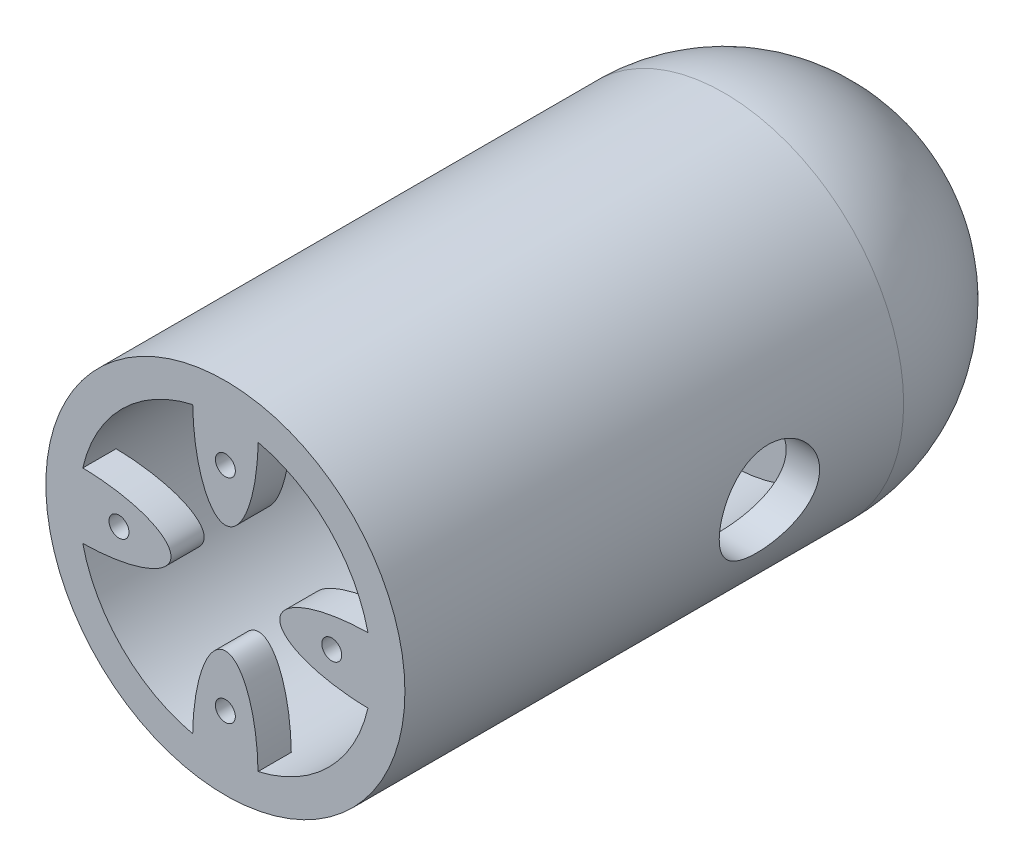
SolidWorks part; units mm, degrees
ref_plane "Front Plane" through (0, 0, 0) normal (0, 0, 1) x (1, 0, 0)
ref_plane "Top Plane" through (0, 0, 0) normal (0, 1, 0) x (1, 0, 0)
ref_plane "Right Plane" through (0, 0, 0) normal (1, 0, 0) x (0, 0, -1)
sketch "Sketch1" plane through (0, 0, 0) normal (0, 0, 1) x (1, 0, 0)
  circle A0 centre (0, 0) radius 27
  dimension "D1" = 54
extrude "Boss-Extrude1" add sketch "Sketch1" along normal mid plane 75
sketch "Sketch3" plane through (0, 0, 0) normal (1, 0, 0) x (0, 0, -1)
  line L1 (37.5, 27) -> (-37.5, 27) construction
  line L2 (37.5, -27) -> (37.5, 27) construction
  circle A0 centre (17.5, -3) radius 7.5
  dimension "D1" = 15
  dimension "D2" = 20
  dimension "D3" = 30
extrude "Cut-Extrude2" cut sketch "Sketch3" against normal through all and the other way through all
sketch "Sketch7" plane through (0, 0, -37.5) normal (0, 0, -1) x (-1, 0, 0)
  line L0 (0, 27) -> (0, -27) construction
  line L1 (0, 27) -> (0, -27)
  arc A0 (0, 27) -> (0, -27) centre (0, 0) ccw
  dimension "D1" = 54
revolve "Revolve1" add sketch "Sketch7" angle 180 about L0
sketch "Sketch2" plane through (0, 0, 37.5) normal (0, 0, 1) x (1, 0, 0)
  circle A0 centre (0, 0) radius 22
  dimension "D1" = 44
extrude "Cut-Extrude3" cut sketch "Sketch2" against normal blind 76
sketch "Sketch13" plane through (0, 0, 37.5) normal (0, 0, 1) x (1, 0, 0)
  circle A0 centre (0, 0) radius 22 construction
  arc A1 (-21.4445, 4.9124) -> (-21.4445, -4.9124) centre (0, 0) ccw
  circle A2 centre (-16, 0) radius 1.5
  ellipse E0 centre (-22, 0) end of major axis (-35.8134, 0) minor radius 4.9164 (-21.4445, -4.9124) -> (-21.4445, 4.9124) ccw
  dimension "D1" = 3
  dimension "D2" = 16
extrude "Boss-Extrude3" add sketch "Sketch13" against normal blind 5
pattern_circular "CirPattern1" count 4 over 360 about axis through (0, 0, 37.5) along (0, 0, -1) of "Boss-Extrude3"
